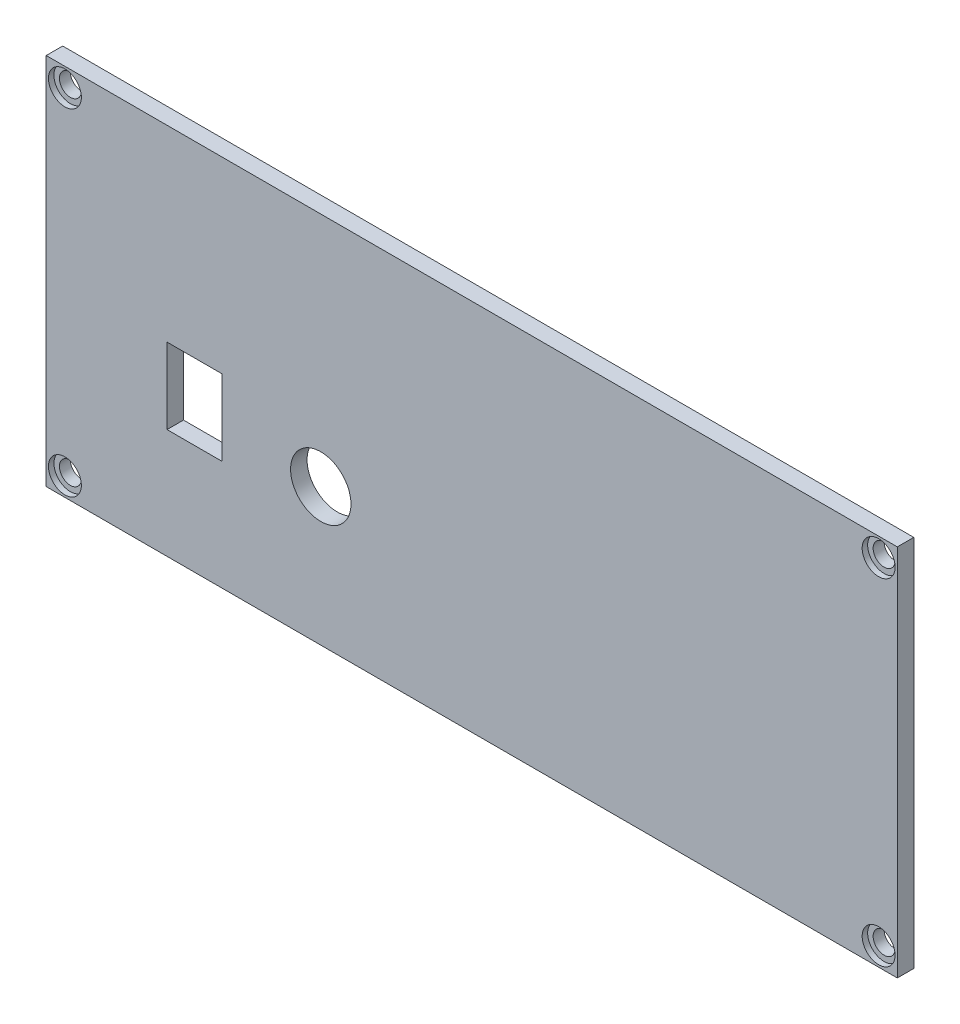
SolidWorks part; units mm, degrees
ref_plane "Ön Düzlem" through (0, 0, 0) normal (0, 0, 1) x (1, 0, 0)
ref_plane "Üst Düzlem" through (0, 0, 0) normal (0, 1, 0) x (1, 0, 0)
ref_plane "Sağ Düzlem" through (0, 0, 0) normal (1, 0, 0) x (0, 0, -1)
sketch "Çizim1" plane through (0, 0, 0) normal (0, 0, 1) x (1, 0, 0)
  line L1 (0, 0) -> (-155, 0)
  line L2 (0, 0) -> (0, 68)
  line L3 (0, 68) -> (-155, 68)
  line L4 (-155, 0) -> (-155, 68)
  dimension "D1" = 155
  dimension "D2" = 68
extrude "Yükseklik-Ekstrüzyon1" add sketch "Çizim1" along normal blind 3
sketch "Çizim2" plane through (0, 0, 3) normal (0, 0, 1) x (1, 0, 0)
  line L0 (-155, 68) -> (-155, 0) construction
  line L1 (-133, 33.8) -> (-123, 33.8)
  line L2 (-133, 33.8) -> (-133, 20)
  line L3 (-133, 20) -> (-123, 20)
  line L4 (-123, 33.8) -> (-123, 20)
  line L5 (-155, 0) -> (0, 0) construction
  circle A0 centre (-105, 25) radius 5.5
  point P10 (0, 0)
  point P12 (-155, 27.6024)
  dimension "D5" = 11
  dimension "D1" = 13.8
  dimension "D2" = 10
  dimension "D3" = 22
  dimension "D4" = 20
  dimension "D6" = 25
  dimension "D7" = 50
extrude "Kes-Ekstrüzyon1" cut sketch "Çizim2" against normal blind 3
sketch "Çizim3" plane through (0, 0, 3) normal (0, 0, 1) x (1, 0, 0)
  line L0 (0, 68) -> (-155, 68) construction
  line L1 (-155, 68) -> (-155, 0) construction
  line L2 (-77.5, 68) -> (-77.5, 0) construction
  line L3 (-155, 0) -> (0, 0) construction
  line L4 (0, 34) -> (-155, 34) construction
  line L5 (0, 0) -> (0, 68) construction
  circle A0 centre (-151.6, 64.6) radius 2
  circle A1 centre (-3.4, 64.6) radius 2
  circle A2 centre (-151.6, 3.4) radius 2
  circle A3 centre (-3.4, 3.4) radius 2
  dimension "D1" = 4
  dimension "D2" = 3.4
  dimension "D3" = 3.4
extrude "Kes-Ekstrüzyon2" cut sketch "Çizim3" against normal blind 3
sketch "Çizim4" plane through (0, 0, 3) normal (0, 0, 1) x (1, 0, 0)
  line L0 (-77.5, 68) -> (-77.5, 0) construction
  line L1 (0, 68) -> (-155, 68) construction
  line L2 (-155, 0) -> (0, 0) construction
  line L3 (-155, 68) -> (-155, 0) construction
  line L4 (-155, 34) -> (0, 34) construction
  line L5 (0, 0) -> (0, 68) construction
  circle A0 centre (-151.6, 64.6) radius 3
  circle A1 centre (-3.4, 64.6) radius 3
  circle A2 centre (-3.4, 3.4) radius 3
  circle A3 centre (-151.6, 3.4) radius 3
  dimension "D1" = 6
extrude "Kes-Ekstrüzyon3" cut sketch "Çizim4" against normal blind 1
